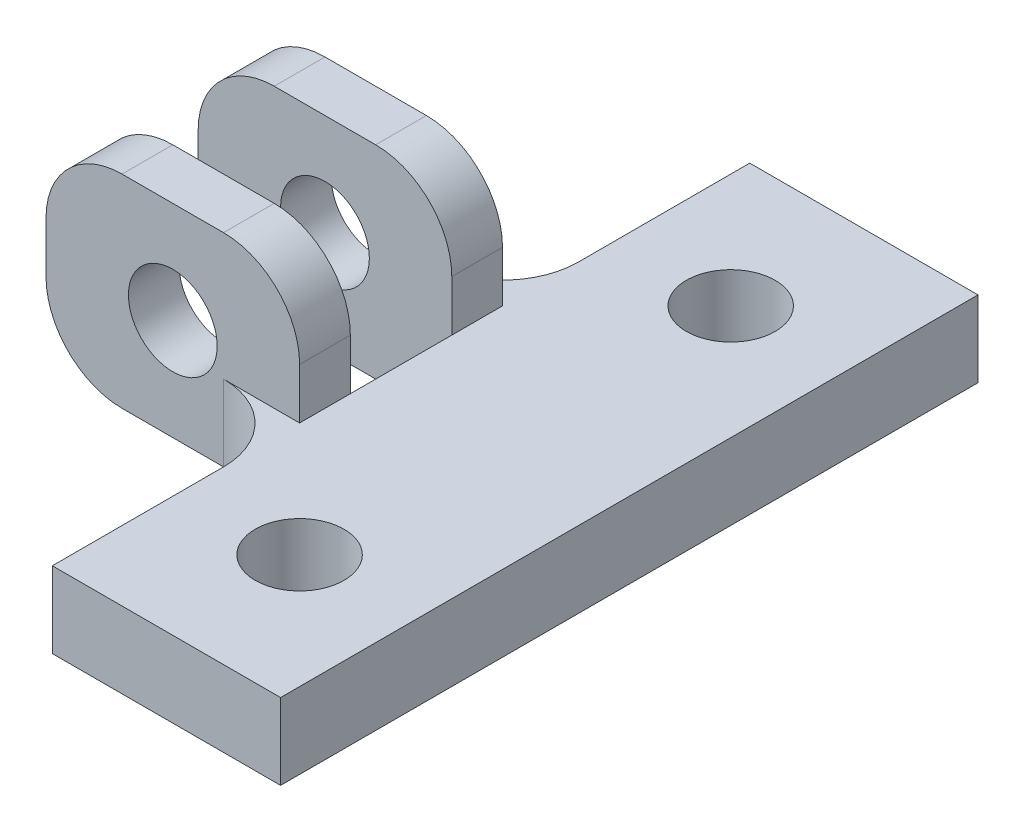
SolidWorks part; units mm, degrees
ref_plane "前视基准面" through (0, 0, 0) normal (0, 0, 1) x (1, 0, 0)
ref_plane "上视基准面" through (0, 0, 0) normal (0, 1, 0) x (1, 0, 0)
ref_plane "右视基准面" through (0, 0, 0) normal (1, 0, 0) x (0, 0, -1)
sketch "草图1" plane through (0, 0, 0) normal (0, 1, 0) x (1, 0, 0)
  line L0 (0, 0) -> (0, 8.7182) construction
  line L1 (-24, 13.75) -> (24, 13.75) construction
  line L2 (-24, 13.75) -> (-24, -13.75) construction
  line L3 (-24, -13.75) -> (24, -13.75) construction
  line L4 (24, 13.75) -> (24, -13.75) construction
  line L5 (-24, 13.75) -> (24, -13.75) construction
  line L6 (-24, -13.75) -> (24, 13.75) construction
  line L7 (0, 8.7182) -> (0, 0) construction
  line L8 (0, 0) -> (11.7869, 0) construction
  line L10 (-24, 13.75) -> (-15, 13.75)
  line L11 (-24, 13.75) -> (-24, -13.75)
  line L12 (-24, -13.75) -> (-15, -13.75)
  line L13 (-15, 13.75) -> (-15, -13.75)
  circle A0 centre (-19.5, 8.5) radius 2.4976 construction
  circle A1 centre (-19.5, -8.5) radius 2.4976 construction
  circle A2 centre (19.5, -8.5) radius 2.4976 construction
  circle A3 centre (19.5, 8.5) radius 2.4976 construction
  circle A4 centre (-19.5, 8.5) radius 1.75
  circle A5 centre (-19.5, -8.5) radius 1.75
  point P0 (0, 0)
  dimension "D3" = 39
  dimension "D4" = 17
  dimension "D6" = 3.5
  dimension "D7" = 3.5
  dimension "D1" = 27.5
  dimension "D2" = 48
  dimension "D5" = 9
extrude "凸台-拉伸1" add sketch "草图1" along normal blind 3
sketch "草图2" plane through (-24, 0, 0) normal (-1, 0, 0) x (0, 0, 1)
  line L0 (-13.75, 0) -> (13.75, 3) construction
  line L1 (-13.75, 0) -> (13.75, 0) construction
  line L2 (-2, 3) -> (2, 3) construction
  line L3 (-2, 3) -> (-2, 0) construction
  line L4 (-2, 0) -> (2, 0) construction
  line L5 (2, 3) -> (2, 0) construction
  line L6 (-2, 3) -> (2, 0) construction
  line L7 (-2, 0) -> (2, 3) construction
  line L9 (-2, 3) -> (-4, 3)
  line L10 (-2, 3) -> (-2, 0)
  line L11 (-2, 0) -> (-4, 0)
  line L12 (-4, 3) -> (-4, 0)
  line L13 (2, 3) -> (4, 3)
  line L14 (2, 3) -> (2, 0)
  line L15 (2, 0) -> (4, 0)
  line L16 (4, 3) -> (4, 0)
  point P4 (0, 1.5)
  dimension "D1" = 4
  dimension "D2" = 2
  dimension "D3" = 2
extrude "凸台-拉伸2" add sketch "草图2" along normal blind 10
sketch "草图3" plane through (0, 0, 0) normal (0, -1, 0) x (1, 0, 0)
  line L1 (-34, 4) -> (-24, 4)
  line L2 (-34, 4) -> (-34, 2)
  line L3 (-34, 2) -> (-24, 2)
  line L4 (-24, 4) -> (-24, 2)
  line L5 (-34, -2) -> (-24, -2)
  line L6 (-34, -2) -> (-34, -4)
  line L7 (-34, -4) -> (-24, -4)
  line L8 (-24, -2) -> (-24, -4)
extrude "凸台-拉伸3" add sketch "草图3" against normal blind 8
sketch "草图4" plane through (0, 0, -4) normal (0, 0, -1) x (-1, 0, 0)
  line L0 (24, 8) -> (34, 0) construction
  circle A0 centre (29, 4) radius 1.75
  dimension "D1" = 3.5
extrude "切除-拉伸1" cut sketch "草图4" against normal through all both and the other way through all
fillet "圆角2" radius 3 8 edges at (-24, 1.5, -4) (-24, 8, 3) (-24, 8, -3) (-34, 8, 3) (-34, 8, -3) (-34, 0, -3) (-34, 0, 3) (-24, 1.5, 4)
